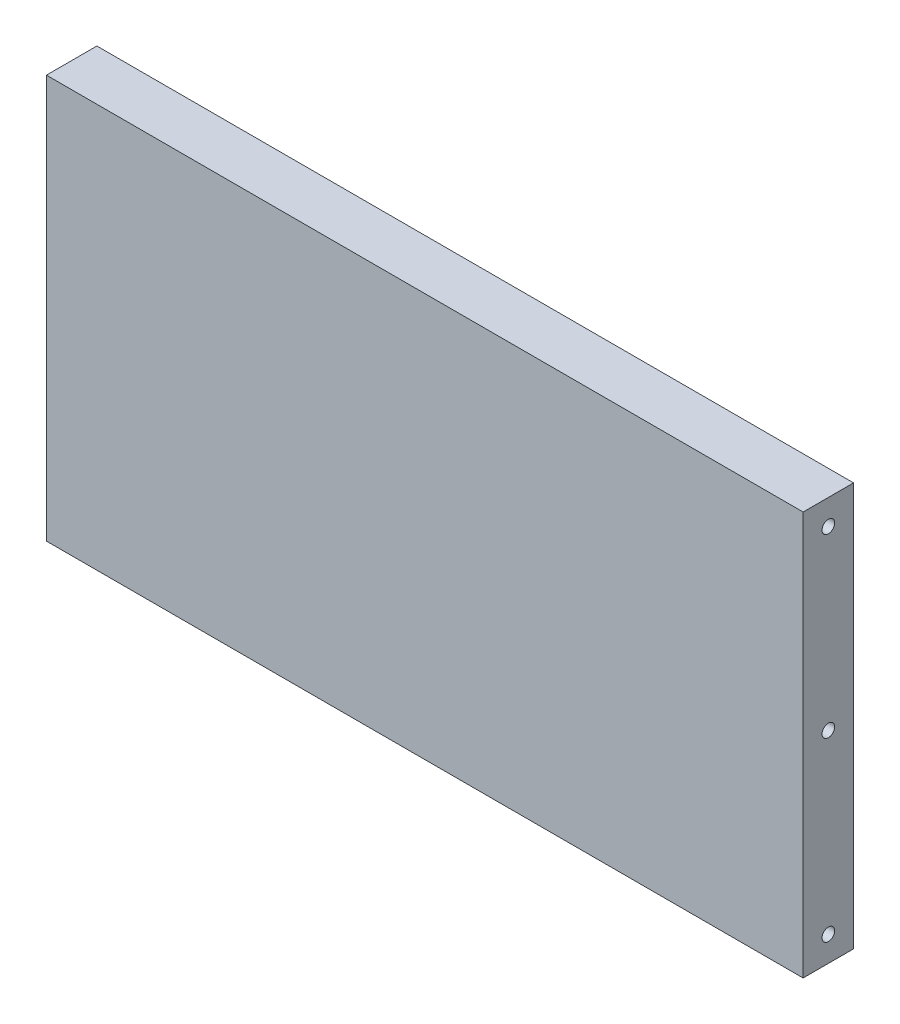
SolidWorks part; units mm, degrees
material "AISI 1020"
ref_plane "Ebene vorne" through (0, 0, 0) normal (0, 0, 1) x (1, 0, 0)
ref_plane "Ebene oben" through (0, 0, 0) normal (0, 1, 0) x (1, 0, 0)
ref_plane "Ebene rechts" through (0, 0, 0) normal (1, 0, 0) x (0, 0, -1)
sketch "Skizze1" plane through (0, 0, 0) normal (0, 0, 1) x (1, 0, 0)
  line L1 (-65.5556, 65.2273) -> (84.4444, 65.2273)
  line L2 (-65.5556, 65.2273) -> (-65.5556, -14.7727)
  line L3 (-65.5556, -14.7727) -> (84.4444, -14.7727)
  line L4 (84.4444, 65.2273) -> (84.4444, -14.7727)
  dimension "D1" = 150
  dimension "D2" = 80
extrude "Aufsatz-Linear austragen1" add sketch "Skizze1" along normal blind 10
sketch "Skizze2" plane through (-65.5556, 0, 0) normal (-1, 0, 0) x (0, 0, 1)
  line L0 (5, 60.2273) -> (5, -9.7727) construction
  line L1 (10, 65.2273) -> (0, 65.2273) construction
  line L2 (10, -14.7727) -> (0, -14.7727) construction
  line L3 (0, 65.2273) -> (0, -14.7727) construction
  circle A0 centre (5, 60.2273) radius 1.25
  circle A1 centre (5, 25.2273) radius 1.25
  circle A2 centre (5, -9.7727) radius 1.25
  dimension "D4" = 2.5
  dimension "D1" = 5
  dimension "D2" = 5
  dimension "D3" = 5
extrude "Schnitt-Linear austragen1" cut sketch "Skizze2" against normal blind 5
sketch "Skizze3" plane through (84.4444, 0, 0) normal (1, 0, 0) x (0, 0, -1)
  line L0 (-5, 60.2273) -> (-5, -9.7727) construction
  line L1 (-10, -14.7727) -> (-10, 65.2273) construction
  line L2 (-10, 65.2273) -> (0, 65.2273) construction
  line L3 (-10, -14.7727) -> (0, -14.7727) construction
  circle A0 centre (-5, 60.2273) radius 1.25
  circle A1 centre (-5, 25.2273) radius 1.25
  circle A2 centre (-5, -9.7727) radius 1.25
  dimension "D1" = 2.5
  dimension "D2" = 5
  dimension "D3" = 5
  dimension "D4" = 5
extrude "Schnitt-Linear austragen2" cut sketch "Skizze3" against normal blind 5
